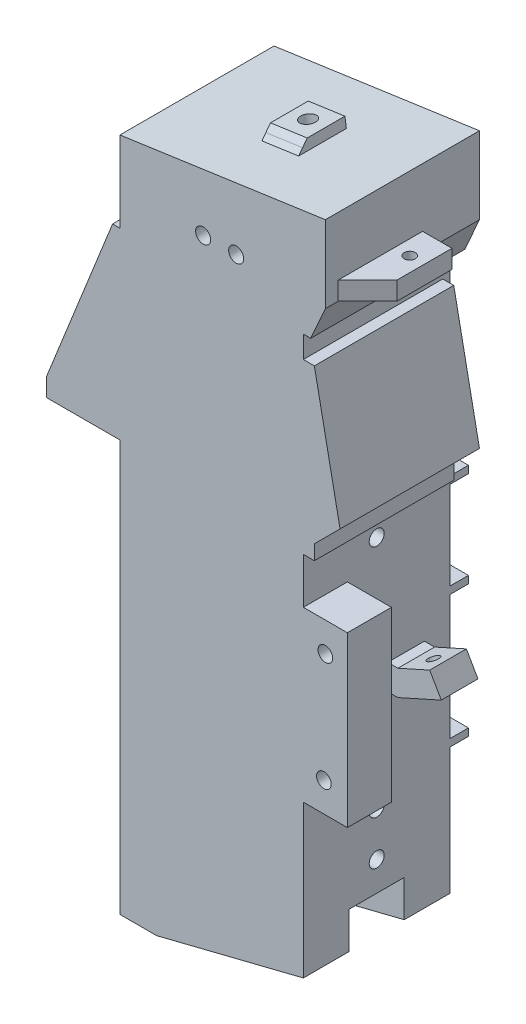
SolidWorks part; units mm, degrees
ref_plane "Alzado" through (0, 0, 0) normal (0, 0, 1) x (1, 0, 0)
ref_plane "Planta" through (0, 0, 0) normal (0, 1, 0) x (1, 0, 0)
ref_plane "Vista lateral" through (0, 0, 0) normal (1, 0, 0) x (0, 0, -1)
sketch "Croquis1" plane through (0, 0, 0) normal (0, 0, 1) x (1, 0, 0)
  line L1 (-25, -92) -> (25, -92)
  line L2 (-25, -92) -> (-25, 92)
  line L3 (-25, 92) -> (25, 92)
  line L4 (25, -92) -> (25, 92)
  line L5 (-25, -92) -> (25, 92) construction
  line L6 (-25, 92) -> (25, -92) construction
  point P0 (0, 0)
  dimension "D1" = 184
  dimension "D2" = 50
extrude "Saliente-Extruir1" add sketch "Croquis1" along normal blind 40
sketch "Croquis2" plane through (0, 0, 40) normal (0, 0, 1) x (1, 0, 0)
  line L0 (-25, -92) -> (-15, -92)
  line L1 (-25, -92) -> (25, -92) construction
  line L2 (-15, -92) -> (25, -82.0002)
  line L3 (25, -92) -> (25, 92) construction
  line L4 (25, -82.0002) -> (25, -92)
  line L5 (25, -92) -> (-15, -92)
  dimension "D1" = 10
  dimension "D2" = 41.231
extrude "Cortar-Extruir1" cut sketch "Croquis2" against normal blind 40 contours L2 L4 L5
sketch "Croquis3" plane through (0, 0, 40) normal (0, 0, 1) x (1, 0, 0)
  line L0 (25, -82.0002) -> (25, -40.5002)
  line L1 (25, -82.0002) -> (25, 92) construction
  line L2 (25, -40.5002) -> (17.2579, -40.5002)
  line L3 (25, -40.5002) -> (37, -40.5002)
  line L5 (23, 5.4998) -> (37, 5.4998)
  line L6 (37, -40.5002) -> (37, 5.4998)
  line L7 (17.2579, -40.5002) -> (17.2579, 5.4998)
  line L8 (17.2579, 5.4998) -> (23, 5.4998)
  circle A0 centre (30.6, -32.5002) radius 2
  circle A1 centre (31, -2.5002) radius 2
  line M8 (25, -82.0002) -> (25, 92)
  dimension "D4" = 4
  dimension "D7" = 8
  dimension "D1" = 41.5
  dimension "D2" = 12
  dimension "D3" = 46
  dimension "D5" = 6
  dimension "D6" = 30
extrude "Saliente-Extruir2" add sketch "Croquis3" against normal through all contours L3 L6 L5 A1 A0 M8 | L8 L7 L2 M8
sketch "Croquis4" plane through (0, 0, 40) normal (0, 0, 1) x (1, 0, 0)
  line L0 (25, 5.4998) -> (25, 17.9998)
  line L1 (25, 5.4998) -> (25, 92) construction
  line L2 (25, 17.9998) -> (28, 17.9998)
  line L3 (28, 17.9998) -> (28, 21.9998)
  line L4 (28, 21.9998) -> (34.9997, 28.9994)
  line L5 (34.9997, 28.9994) -> (27.9996, 63.9993)
  line L6 (27.9996, 63.9993) -> (25, 63.9993)
  line L7 (25, 63.9993) -> (25, 17.9998)
  line L8 (25, 63.9993) -> (25, 69.9993)
  line L9 (25, 69.9993) -> (27, 69.9993)
  line L10 (27, 69.9993) -> (31.0001, 78.9994)
  line L11 (31.0001, 78.9994) -> (42.3141, 78.9994)
  line L12 (42.3141, 78.9994) -> (42.3141, 83.9994)
  line L13 (42.3141, 83.9994) -> (31.0001, 83.9994)
  line L14 (25, 92) -> (31.0001, 92)
  line L15 (31.0001, 92) -> (31.0001, 83.9994)
  line L16 (25, 69.9993) -> (25, 92)
  dimension "D1" = 12.5
  dimension "D2" = 3
  dimension "D3" = 4
  dimension "D4" = 9.899
  dimension "D5" = 135
  dimension "D6" = 35.693
  dimension "D7" = 123.69
  dimension "D8" = 6
  dimension "D9" = 2
  dimension "D10" = 9.849
  dimension "D11" = 113.963
  dimension "D12" = 11.314
  dimension "D13" = 5
sketch "Croquis7" plane through (0, 0, 0) normal (0, 0, -1) x (-1, 0, 0)
  line L0 (-25, 17.9998) -> (-28, 17.9998)
  line L1 (-28, 17.9998) -> (-28, 21.9998)
  line L2 (-28, 21.9998) -> (-34.9997, 28.9994)
  line L3 (-34.9997, 28.9994) -> (-27.9996, 63.9993)
  line L4 (-27.9996, 63.9993) -> (-25, 63.9993)
  line L5 (-25, 63.9993) -> (-25, 17.9998)
extrude "Saliente-Extruir3" add sketch "Croquis7" against normal blind 38
sketch "Croquis8" plane through (0, 0, 0) normal (0, 0, -1) x (-1, 0, 0)
  line L0 (-25, 69.9993) -> (-27, 69.9993)
  line L1 (-27, 69.9993) -> (-31.0001, 78.9994)
  line L2 (-31.0001, 78.9994) -> (-42.3141, 78.9994)
  line L3 (-42.3141, 78.9994) -> (-42.3141, 83.9994)
  line L4 (-42.3141, 83.9994) -> (-31.0001, 83.9994)
  line L5 (-31.0001, 83.9994) -> (-31.0001, 92)
  line L6 (-31.0001, 92) -> (-25, 92)
  line L7 (-25, 92) -> (-25, 69.9993)
extrude "Saliente-Extruir4" add sketch "Croquis8" against normal through all
sketch "Croquis9" plane through (37, 0, 0) normal (1, 0, 0) x (0, 0, -1)
  line L0 (0, -40.5002) -> (-40, -40.5002) construction
  line L4 (-12, 5.4998) -> (-12, -40.5002)
  line L5 (-12, 5.4998) -> (-40, 5.4998)
  line L6 (-40, 5.4998) -> (-40, -40.5002)
  line L7 (-40, -40.5002) -> (-12, -40.5002)
extrude "Cortar-Extruir6" cut sketch "Croquis9" against normal blind 12
sketch "Croquis10" plane through (0, 78.9994, 0) normal (0, -1, 0) x (1, 0, 0)
  line L0 (31.0001, 40) -> (31.0001, 26.5)
  line L1 (31.0001, 40) -> (31.0001, 0) construction
  line L2 (31.0001, 26.5) -> (39.0001, 26.5)
  line L3 (39.0001, 26.5) -> (39.0001, 11.5)
  line L4 (39.0001, 11.5) -> (30.9999, 3.4998)
  line L6 (31.0001, 40) -> (42.3141, 40)
  line L7 (42.3141, 40) -> (42.3141, 0)
  line L9 (30.9999, 3.4998) -> (31.0001, 0)
  line L10 (31.0001, 0) -> (42.3141, 0)
  dimension "D1" = 13.5
  dimension "D2" = 8
  dimension "D3" = 15
  dimension "D4" = 135
  dimension "D5" = 11.314
extrude "Cortar-Extruir8" cut sketch "Croquis10" against normal blind 12
sketch "Croquis13" plane through (31.0001, 0, 0) normal (1, 0, 0) x (0, 0, -1)
  line L0 (0, 90.9994) -> (-3.4998, 90.9994)
  line L1 (-3.4998, 90.9994) -> (-3.4998, 78.9994)
  line L2 (-3.4998, 78.9994) -> (0, 78.9994)
  line L3 (0, 78.9994) -> (0, 90.9994)
extrude "Saliente-Extruir5" add sketch "Croquis13" against normal blind 12
sketch "Croquis14" plane through (0, 78.9994, 0) normal (0, -1, 0) x (1, 0, 0)
  line L0 (39.0001, 26.5) -> (39.0001, 11.5) construction
  line L1 (31.0001, 26.5) -> (39.0001, 26.5) construction
  circle A0 centre (35.0001, 19) radius 1.5
  dimension "D1" = 3
  dimension "D2" = 4
  dimension "D3" = 7.5
extrude "Cortar-Extruir9" cut sketch "Croquis14" against normal blind 12
sketch "Croquis16" plane through (25, 0, 0) normal (1, 0, 0) x (0, 0, -1)
  line L0 (0, -82.0002) -> (-40, -82.0002) construction
  line L1 (-33, -25.9192) -> (-23, -25.9192)
  line L2 (-33, -25.9192) -> (-33, -18.9912)
  line L3 (-33, -18.9912) -> (-23, -18.9912)
  line L4 (-23, -25.9192) -> (-23, -18.9912)
  line L5 (-40, -82.0002) -> (-40, 69.9993) construction
  dimension "D1" = 56.081
  dimension "D2" = 10
  dimension "D3" = 7
  dimension "D4" = 6.928
extrude "Saliente-Extruir6" add sketch "Croquis16" along normal blind 2.773
sketch3d "Croquis3D1"
  line L0 (27.773, -25.9192, 28) -> (39.597, -20.6034, 28)
  line L1 (27.773, -25.9192, 33) -> (27.773, -25.9192, 23) construction
  line L2 (27.773, -18.9912, 28) -> (36.4376, -15.0958, 28)
  line L3 (27.773, -18.9912, 23) -> (27.773, -18.9912, 33) construction
  line L4 (39.597, -20.6034, 28) -> (36.4376, -15.0958, 28)
  line L5 (27.773, -25.9192, 28) -> (27.773, -18.9912, 28)
  dimension "D1" = 12.964
  dimension "D2" = 9.5
extrude "Saliente-Extruir7" add sketch "Croquis3D1" along direction (0, 0, -1) on the side of the normal mid plane 10 contours L2 L4 L0 L5
sketch "Croquis19" plane through (14.363, -31.948, 0) normal (0.41, -0.9121, 0) x (0.9121, 0.41, 0)
  line L0 (27.6668, 23) -> (27.6668, 33) construction
  line L1 (14.7028, 23) -> (27.6668, 23) construction
  circle A0 centre (22.6668, 28) radius 1.5
  dimension "D1" = 3
  dimension "D3" = 5
  dimension "D2" = 5
extrude "Cortar-Extruir10" cut sketch "Croquis19" against normal blind 10
sketch "Croquis20" plane through (0, -92, 0) normal (0, -1, 0) x (1, 0, 0)
  line L0 (-15, 12.5) -> (-15, 27.5)
  line L1 (-15, 0) -> (-15, 40) construction
  line L2 (-15, 27.5) -> (25, 27.5)
  line L3 (25, 33) -> (25, 23) construction
  line L4 (25, 27.5) -> (25, 12.5)
  line L5 (25, 38) -> (25, 0) construction
  line L6 (25, 12.5) -> (-15, 12.5)
  line L7 (-15, 0) -> (25, 0) construction
  line L8 (-15, 40) -> (25, 40) construction
  point P5 (-15, 20)
  dimension "D1" = 12.5
  dimension "D2" = 12.5
extrude "Cortar-Extruir11" cut sketch "Croquis20" against normal blind 20
sketch "Croquis21" plane through (0, 0, 0) normal (0, 0, -1) x (-1, 0, 0)
  line L0 (25, 92) -> (25, 70) construction
  line L1 (25, 92) -> (25, -92) construction
  line L2 (25, 70) -> (27, 70)
  line L3 (25, -92) -> (25, 20) construction
  line L4 (25, 20) -> (45, 20)
  line L5 (45, 20) -> (45, 25)
  line L6 (27, 70) -> (45, 25)
  line L7 (25, 70) -> (25, 20)
  dimension "D1" = 22
  dimension "D2" = 2
  dimension "D3" = 112
  dimension "D4" = 20
  dimension "D5" = 5
extrude "Saliente-Extruir8" add sketch "Croquis21" against normal blind 40
sketch "Croquis22" plane through (0, 0, 40) normal (0, 0, 1) x (1, 0, 0)
  line L0 (31.0001, 92) -> (31.0001, 99.9994)
  line L2 (-25, 92) -> (31.0001, 99.9994)
  line L3 (-25, 92) -> (31.0001, 92)
  line L4 (31.0001, 92) -> (31.0001, 99.9994)
  line M4 (31.0001, 92) -> (-25, 92)
extrude "Saliente-Extruir9" add sketch "Croquis22" against normal blind 40 contours L2 L0 M4
sketch "Croquis23" plane through (0, 0, 40) normal (0, 0, 1) x (1, 0, 0)
  line L0 (-25, 70) -> (25, 69.9993)
  line L1 (25, 69.9993) -> (27, 69.9993)
  line L2 (27, 69.9993) -> (31.0001, 78.9994)
  line L3 (31.0001, 78.9994) -> (31.0001, 99.9994)
  line L4 (31.0001, 99.9994) -> (-25, 92)
  line L5 (-25, 92) -> (-25, 70)
extrude "Saliente-Extruir10" add sketch "Croquis23" along normal blind 2
sketch "Croquis25" plane through (0, 70, 0) normal (0, 1, 0) x (1, 0, 0)
  line L0 (-27, -40) -> (-27, -27.5)
  line L1 (-27, -40) -> (-27, 0) construction
  line L2 (-27, -27.5) -> (-45, -27.5)
  line L3 (-45, -40) -> (-45, 0) construction
  line L4 (-45, -27.5) -> (-45, -12.5)
  line L5 (-45, -12.5) -> (-27, -12.5)
  line L6 (-27, -12.5) -> (-27, -27.5)
  line L7 (-45, 0) -> (-27, 0) construction
  line M4 (-27, 0) -> (-27, -40)
  dimension "D1" = 12.5
  dimension "D2" = 12.5
extrude "Cortar-Extruir12" cut sketch "Croquis25" against normal blind 45 contours L5 L4 L2 M4
sketch "Croquis26" plane through (0, 25, 0) normal (0, 1, 0) x (1, 0, 0)
  line L0 (-45, -20) -> (-27, -20) construction
  line L1 (-45, -27.5) -> (-45, -12.5) construction
  line L2 (-27, -12.5) -> (-27, -27.5) construction
  circle A0 centre (-36, -20) radius 1.6
  dimension "D1" = 3.2
extrude "Cortar-Extruir13" cut sketch "Croquis26" against normal blind 45
sketch "Croquis28" plane through (0, 0, 40) normal (0, 0, 1) x (1, 0, 0)
  line L0 (-30.431, 20) -> (18, 20)
  line L2 (-25, -92) -> (-15, -92) construction
  line L3 (25, -82.0002) -> (25, 69.9993) construction
  line L4 (18, 20) -> (18, 63)
  line L5 (18, 63) -> (-18.529, 63)
  line L6 (-30.431, 20) -> (-30.431, 43.969)
  line L7 (-30.431, 43.969) -> (-18.529, 63)
  dimension "D1" = 112
  dimension "D2" = 7
  dimension "D3" = 48.431
  dimension "D4" = 43
  dimension "D5" = 36.529
  dimension "D6" = 23.969
extrude "Saliente-Extruir11" add sketch "Croquis28" along normal blind 1
sketch "Croquis29" plane through (0, 0, 41) normal (0, 0, 1) x (1, 0, 0)
  line L0 (18, 20) -> (18, 21.5)
  line L1 (-18.529, 63) -> (-15.919, 63)
  line L2 (18, 20) -> (18, 63) construction
  line L3 (18, 21.5) -> (-30.431, 21.5)
  line L4 (-30.431, 43.969) -> (-30.431, 20) construction
  line L5 (-30.431, 21.5) -> (-30.431, 20)
  line L6 (-30.431, 20) -> (18, 20)
  line L7 (-30.431, 21.5) -> (-22.6197, 21.5)
  line L8 (18, 63) -> (-18.529, 63) construction
  line L9 (-15.919, 63) -> (-15.919, 21.5)
  line L10 (-15.919, 21.5) -> (-14.419, 21.5)
  line L11 (-14.419, 21.5) -> (-14.419, 63)
  line L12 (18, 63) -> (-18.529, 63) construction
  line L13 (-14.419, 63) -> (-15.919, 63)
  line L14 (-15.919, 63) -> (-15.919, 47.99)
  line L15 (-15.919, 47.99) -> (18, 47.99)
  line L16 (18, 47.99) -> (18, 46.49)
  line L17 (18, 20) -> (18, 63) construction
  line L18 (18, 46.49) -> (-28.8544, 46.49)
  line L19 (-18.529, 63) -> (-30.431, 43.969) construction
  line L20 (-15.919, 47.99) -> (-27.9163, 47.99)
  line L21 (-18.529, 63) -> (-30.431, 43.969) construction
  line L22 (-27.9163, 47.99) -> (-28.8544, 46.49)
  dimension "D1" = 1.5
  dimension "D2" = 2.61
  dimension "D3" = 1.5
  dimension "D4" = 15.01
  dimension "D5" = 1.5
extrude "Saliente-Extruir12" add sketch "Croquis29" along normal blind 1 contours L9 L10 L11 L13 | L15 L16 L18 L22 L20 | L5 L6 L0 L3
sketch "Croquis30" plane through (0, 0, 40) normal (0, 0, 1) x (1, 0, 0)
  line L0 (25, 16.538) -> (-25, 16.538)
  line L1 (-25, 20) -> (18, 20) construction
  line L2 (25, -82.0002) -> (25, 69.9993) construction
  line L3 (-25, 20) -> (-25, -92) construction
  line L4 (-25, 16.538) -> (-25, 14.538)
  line L5 (-25, 14.538) -> (25, 14.538)
  line L6 (25, 14.538) -> (25, 16.538)
  dimension "D1" = 3.462
  dimension "D2" = 2
extrude "Saliente-Extruir13" add sketch "Croquis30" along normal blind 5 contours L6 L0 L4 L5
sketch "Croquis31" plane through (0, 14.538, 0) normal (0, -1, 0) x (1, 0, 0)
  line L0 (-25, 40) -> (-20.0001, 45)
  line L1 (-25, 45) -> (25, 45) construction
  line L2 (-20.0001, 45) -> (8.4619, 45)
  line L3 (8.4619, 45) -> (25, 40)
  line L4 (25, 40) -> (-25, 40)
  dimension "D1" = 7.071
  dimension "D2" = 28.462
extrude "Saliente-Extruir14" add sketch "Croquis31" along normal blind 24
sketch "Croquis32" plane through (0, 0, 45) normal (0, 0, 1) x (1, 0, 0)
  line L0 (-20.0001, 14.538) -> (-25, 7.4672)
  line L1 (-25, 14.538) -> (-25, -9.462) construction
  line L2 (-25, 7.4672) -> (-25, 14.538)
  line L3 (-25, 14.538) -> (-20.0001, 14.538)
  dimension "D1" = 8.66
extrude "Cortar-Extruir14" cut sketch "Croquis32" against normal blind 5
sketch "Croquis33" plane through (0, -9.462, 0) normal (0, -1, 0) x (1, 0, 0)
  line L0 (-25, 40) -> (-25, 45)
  line L1 (-25, 45) -> (25, 45)
  line L2 (25, 45) -> (25, 40)
  line L3 (25, 40) -> (-25, 40)
extrude "Saliente-Extruir15" add sketch "Croquis33" along normal blind 2
sketch "Croquis34" plane through (0, -11.462, 0) normal (0, -1, 0) x (1, 0, 0)
  line L0 (-25, 40) -> (-9.5194, 45)
  line L1 (25, 45) -> (-25, 45) construction
  line L2 (-9.5194, 45) -> (19.9996, 45)
  line L3 (19.9996, 45) -> (25, 40)
  line L4 (25, 40) -> (-25, 40)
  dimension "D1" = 16.268
  dimension "D2" = 29.519
extrude "Saliente-Extruir16" add sketch "Croquis34" along normal blind 34
sketch "Croquis35" plane through (0, -45.462, 0) normal (0, -1, 0) x (1, 0, 0)
  line L0 (-25, 40) -> (-25, 45)
  line L1 (-25, 45) -> (25, 45)
  line L2 (25, 45) -> (25, 40)
  line L3 (25, 40) -> (-25, 40)
extrude "Saliente-Extruir17" add sketch "Croquis35" along normal blind 2
sketch "Croquis36" plane through (-15, 0, 0) normal (1, 0, 0) x (0, 0, -1)
  line L0 (-20, -92) -> (-20, -72) construction
  line L1 (-27.5, -92) -> (-12.5, -92) construction
  line L2 (-27.5, -72) -> (-12.5, -72) construction
  circle A0 centre (-20, -82) radius 1.6
  dimension "D1" = 3.2
extrude "Cortar-Extruir15" cut sketch "Croquis36" against normal through all
sketch "Croquis37" plane through (25, 0, 0) normal (1, 0, 0) x (0, 0, -1)
  line L0 (-20, -72) -> (-20, -64) construction
  line L1 (-12.5, -72) -> (-27.5, -72) construction
  circle A0 centre (-20, -64) radius 2.05
  circle A1 centre (-20, -52) radius 2.05
  circle A2 centre (-20, 12) radius 2.05
  dimension "D1" = 4.1
  dimension "D2" = 12
  dimension "D3" = 8
  dimension "D4" = 64
extrude "Cortar-Extruir16" cut sketch "Croquis37" against normal blind 6
sketch "Croquis38" plane through (0, 0, 0) normal (0, 0, -1) x (-1, 0, 0)
  line L0 (25, 92) -> (25, 70) construction
  line L1 (25, 92) -> (-31.0001, 99.9994) construction
  circle A0 centre (-6.684, 79.6193) radius 2.05
  circle A1 centre (2.316, 79.6193) radius 2.05
  dimension "D1" = 4.1
  dimension "D4" = 15.464
  dimension "D2" = 9
  dimension "D3" = 22.684
extrude "Cortar-Extruir17" cut sketch "Croquis38" against normal blind 6
sketch "Croquis39" plane through (-13.3789, 93.66, 0) normal (-0.1414, 0.99, 0) x (0.99, 0.1414, 0)
  line L0 (44.8295, -21) -> (22.8295, -21)
  line L2 (44.8295, 0) -> (44.8295, -42) construction
  line L3 (22.8295, -27.5) -> (22.8295, -14.5)
  line L4 (22.8295, -14.5) -> (12.7205, -14.5)
  line L5 (12.7205, -14.5) -> (12.7205, -27.5)
  line L6 (12.7205, -27.5) -> (22.8295, -27.5)
  point P7 (22.8295, -21)
  dimension "D1" = 22
  dimension "D2" = 13
  dimension "D3" = 10.109
extrude "Saliente-Extruir18" add sketch "Croquis39" along normal blind 2.741 contours L5 L6 L3 L4
sketch "Croquis40" plane through (12.5927, 1.7988, 0) normal (-0.99, -0.1414, 0) x (0, 0, 1)
  line L3 (14.5, 94.6108) -> (15.746, 95.8698)
  line L6 (14.5, 97.3518) -> (27.5, 97.3518) construction
  line L7 (15.746, 95.8698) -> (17.211, 97.3518)
  line L8 (17.211, 97.3518) -> (14.5, 97.3518)
  line L9 (14.5, 97.3518) -> (14.5, 94.6108)
extrude "Cortar-Extruir18" cut sketch "Croquis40" against normal through all contours L8 L9 L3 L7
sketch "Croquis42" plane through (-13.7665, 96.3735, 0) normal (-0.1414, 0.99, 0) x (0.99, 0.1414, 0)
  line L0 (12.7205, -27.5) -> (22.8295, -27.5) construction
  line L1 (12.7205, -17.211) -> (12.7205, -27.5) construction
  circle A0 centre (17.7205, -22.5) radius 2.05
  dimension "D1" = 4.1
  dimension "D2" = 5
  dimension "D3" = 5
extrude "Cortar-Extruir19" cut sketch "Croquis42" against normal blind 6
mirror "Simetría1" about plane through (0, 0, 0) normal (0, 0, -1) of "Saliente-Extruir9", "Saliente-Extruir1", "Cortar-Extruir1", "Saliente-Extruir2", "Saliente-Extruir3", "Saliente-Extruir4", "Cortar-Extruir6", "Cortar-Extruir8", "Saliente-Extruir5", "Cortar-Extruir9", "Saliente-Extruir6", "Saliente-Extruir7", "Cortar-Extruir10", "Cortar-Extruir11", "Saliente-Extruir8", "Saliente-Extruir10", "Cortar-Extruir12", "Cortar-Extruir13", "Saliente-Extruir11", "Saliente-Extruir12", "Saliente-Extruir13", "Saliente-Extruir14", "Cortar-Extruir14", "Saliente-Extruir15", "Saliente-Extruir16", "Saliente-Extruir17", "Cortar-Extruir15", "Cortar-Extruir16", "Cortar-Extruir17", "Saliente-Extruir18", "Cortar-Extruir18", "Cortar-Extruir19"
sketch "Croquis43" plane through (31.0001, 0, 0) normal (1, 0, 0) x (0, 0, -1)
  line L0 (42, 99.9994) -> (0, 99.9994)
  line L1 (42, 99.9994) -> (-42, 99.9994) construction
  line L2 (0, 99.9994) -> (0, -92)
  line L3 (12.5, -92) -> (-12.5, -92) construction
  line L4 (0, -92) -> (-89.7159, -92)
  line L5 (-89.7159, -92) -> (-89.7159, 99.9994)
  line L6 (-89.7159, 99.9994) -> (0, 99.9994)
  line M1 (-3.4998, 78.9994) -> (3.4998, 78.9994)
  line M10 (-42, 99.9994) -> (-42, 78.9994)
  line M11 (-42, 78.9994) -> (-26.5, 78.9994)
  line M12 (-26.5, 78.9994) -> (-26.5, 83.9994)
  line M13 (-26.5, 83.9994) -> (-3.5, 83.9994)
  line M14 (-3.5, 83.9994) -> (-3.5, 90.9994)
  line M15 (-3.5, 90.9994) -> (-3.4998, 90.9994)
  line M16 (-3.4998, 90.9994) -> (-3.4998, 78.9994)
extrude "Cortar-Extruir20" cut sketch "Croquis43" against normal through all both and the other way through all contours L6 L5 L4 L2 M1 M16 M15 M14 M13 M12 M11 M10
sketch "Croquis44" plane through (31.0001, 0, 0) normal (1, 0, 0) x (0, 0, -1)
  line L0 (0, 52.9261) -> (0, 138.9314)
  line L1 (0, 63.9993) -> (0, 28.9994) construction
  line L2 (0, 138.9314) -> (-64.641, 138.9314)
  line L3 (-64.641, 138.9314) -> (-64.641, 52.9261)
  line L4 (-64.641, 52.9261) -> (0, 52.9261)
extrude "Cortar-Extruir21" cut sketch "Croquis44" against normal through all
